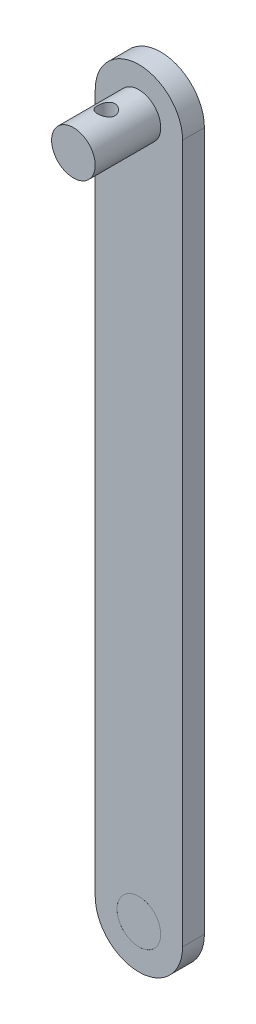
SolidWorks part; units mm, degrees
ref_plane "Front Plane" through (0, 0, 0) normal (0, 0, 1) x (1, 0, 0)
ref_plane "Top Plane" through (0, 0, 0) normal (0, 1, 0) x (1, 0, 0)
ref_plane "Right Plane" through (0, 0, 0) normal (1, 0, 0) x (0, 0, -1)
sketch "Sketch1" plane through (0, 0, 0) normal (0, 0, 1) x (1, 0, 0)
  line L0 (-12.7, -101.6) -> (-12.7, 101.6)
  line L1 (12.7, -101.6) -> (12.7, 101.6)
  line L2 (-22.7949, 0) -> (48.0321, 0) construction
  line L3 (-65.5814, 114.3) -> (65.5814, 114.3) construction
  arc A0 (-12.7, 101.6) -> (12.7, 101.6) centre (0, 101.6) cw
  circle A1 centre (0, 101.6) radius 6.35
  circle A2 centre (0, -101.6) radius 6.35
  arc A3 (-12.7, -101.6) -> (12.7, -101.6) centre (0, -101.6) ccw
  point P2 (-12.7, 0)
  point P13 (12.7, 0)
  point P15 (0, 114.3)
  point P16 (0, 47.785)
  dimension "D1" = 12.7
  dimension "D3" = 12.7
  dimension "D2" = 101.6
  dimension "D4" = 12.7
extrude "Boss-Extrude1" add sketch "Sketch1" along normal blind 6.35
sketch "Sketch2" plane through (0, 0, 0) normal (0, 0, 1) x (1, 0, 0)
  circle A0 centre (0, 101.6) radius 6.35
extrude "Boss-Extrude3" add sketch "Sketch2" along normal blind 25.4
sketch "Sketch4" plane through (0, 0, 0) normal (0, 0, 1) x (1, 0, 0)
  circle A0 centre (0, -101.6) radius 6.35
  dimension "D1" = 12.7
extrude "Boss-Extrude4" add sketch "Sketch4" against normal mid plane 12.7 separate body
sketch "Sketch5" plane through (0, 0, 0) normal (0, 1, 0) x (1, 0, 0)
  line L0 (0, -6.35) -> (0, -25.4) construction
  line L1 (-12.7, -6.35) -> (12.7, -6.35) construction
  line L2 (-6.35, -25.4) -> (6.35, -25.4) construction
  circle A0 centre (0, -15.875) radius 2.54
  point P2 (0, -15.875)
  dimension "D1" = 5.08
extrude "Cut-Extrude2" cut sketch "Sketch5" along normal through all
